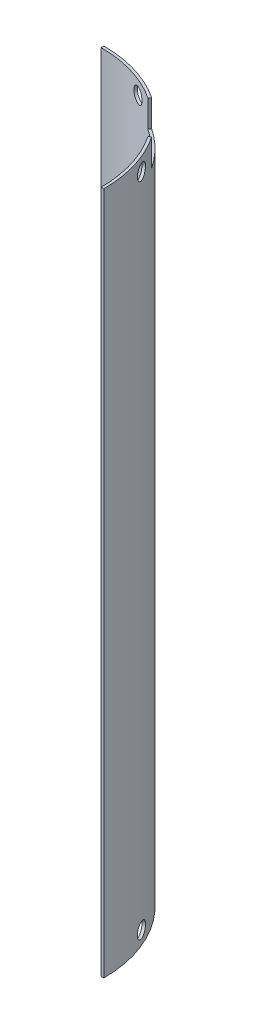
SolidWorks part; units mm, degrees
material "1060 Alloy"
ref_plane "Front Plane" through (0, 0, 0) normal (0, 0, 1) x (1, 0, 0)
ref_plane "Top Plane" through (0, 0, 0) normal (0, 1, 0) x (1, 0, 0)
ref_plane "Right Plane" through (0, 0, 0) normal (1, 0, 0) x (0, 0, -1)
sketch "Sketch1" plane through (0, 0, 0) normal (0, 1, 0) x (1, 0, 0)
  line L0 (0, 0) -> (0, 92)
  line L1 (0, 0) -> (92, 0)
  circle A0 centre (0, 0) radius 90
  circle A1 centre (0, 0) radius 92
  dimension "Internal Diameter" = 180
  dimension "External Diameter" = 184
extrude "Boss-Extrude1" add sketch "Sketch1" along normal blind 508.5 contours L1 A1 L0 A0
ref_plane "Plane1" through (0, 10, 0) normal (0, -1, 0) x (-1, 0, 0)
sketch "Sketch2" plane through (0, 10, 0) normal (0, -1, 0) x (-1, 0, 0)
  line L0 (0, 0) -> (-84.9969, 35.2069)
  line L1 (0, 0) -> (-65.0538, 65.0538)
  line L2 (0, 0) -> (-92, 0) construction
  line L3 (0, 0) -> (-35.2069, 84.9969)
  arc A0 (0, 92) -> (-92, 0) centre (0, 0) ccw construction
  dimension "D1" = 135
  dimension "D2" = 22.5
ref_plane "Plane2" through (84.9969, 0, -35.2069) normal (0.9239, 0, -0.3827) x (-0.3827, 0, -0.9239)
ref_plane "Plane3" through (35.2069, 0, -84.9969) normal (0.3827, 0, -0.9239) x (-0.9239, 0, -0.3827)
sketch "Sketch3" plane through (84.9969, 0, -35.2069) normal (0.9239, 0, -0.3827) x (-0.3827, 0, -0.9239)
  circle A0 centre (0, 10) radius 5.565
  point P0 (0, 10)
  dimension "Right Hole Diameter" = 11.13
sketch "Sketch5" plane through (35.2069, 0, -84.9969) normal (0.3827, 0, -0.9239) x (-0.9239, 0, -0.3827)
  line L0 (0, 10) -> (-84.9969, 10) construction
  circle A0 centre (0, 10) radius 5.565
  dimension "Left Hole Diameter" = 11.13
ref_plane "Plane4" through (65.0538, 0, -65.0538) normal (0.7071, 0, -0.7071) x (-0.7071, 0, -0.7071)
sketch "Sketch6" plane through (65.0538, 0, -65.0538) normal (0.7071, 0, -0.7071) x (-0.7071, 0, -0.7071)
  line L0 (0, 10) -> (-65.0538, 10) construction
  line L1 (0, 10) -> (35.2069, 10) construction
  circle A0 centre (0, 10) radius 5.565
  dimension "Middle Hole Diameter" = 11.13
extrude "Cut-Extrude4" cut sketch "Sketch6" against normal up to surface (2.1722 mm away)
extrude "Cut-Extrude2" cut sketch "Sketch3" against normal up to surface (2.1722 mm away) contours A0
extrude "Cut-Extrude3" cut sketch "Sketch5" against normal up to surface (2.1722 mm away) contours A0
pattern_linear "LPattern2" count 2 spacing 488.5 along (0, 1, 0) of "Cut-Extrude2", "Cut-Extrude3"
sketch "Sketch7" plane through (0, 0, 0) normal (0, -1, 0) x (1, 0, 0)
  line L0 (0, 0) -> (65.0538, -65.0538) construction
  line L1 (0.3118, -0.3118) -> (57.9282, -0.3118) construction
  line L2 (0.3118, -0.3118) -> (76.4474, -51.184)
  line L3 (0.3118, -0.3118) -> (51.184, -76.4474)
  line L6 (92, 0) -> (90, 0)
  line L7 (0, -90) -> (0, -92)
  line L8 (92, 0) -> (90, 0)
  line L9 (0, -90) -> (0, -92)
  arc A0 (0, -92) -> (92, 0) centre (0, 0) ccw construction
  arc A2 (0, -90) -> (90, 0) centre (0, 0) ccw
  arc A3 (0, -92) -> (92, 0) centre (0, 0) ccw
  arc A4 (0, -90) -> (90, 0) centre (0, 0) ccw
  arc A5 (0, -92) -> (92, 0) centre (0, 0) ccw
  arc M5 (90, 0) -> (0, -90) centre (0, 0) cw
  arc M7 (0, -92) -> (92, 0) centre (0, 0) ccw
  dimension "D1" = 45
  dimension "D2" = 11.25
  dimension "D3" = 0
extrude "Cut-Extrude5" cut sketch "Sketch7" against normal blind 20 contours L3 L2 M5 M7
move or copy body "Body-Move/Copy1" bodies to move or copy 107 copy no rotation origin (0, 252, 0) rotation axis (0.7071, 0, -0.7071) rotation angle 180
equation "\"Total Panel Length\"= 508.5"
equation "\"Internal Panel Diameter\"= 180"
equation "\"External Panel Diameter\"= 184"
equation "\"L & R Mounting Hole Diameter\"= 11.13"
equation "\"M Mounting Hole DIameter\" = 11.13"
equation "\"Mounting Hole Dist. from Top\"= 10"
equation "\"Mounting Hole Dist. from Base\" = 10"
equation "\"External Diameter@Sketch1\"= \"External Panel Diameter\""
equation "\"Internal Diameter@Sketch1\"= \"Internal Panel Diameter\""
equation "\"Panel Length@Boss-Extrude1\"= \"Total Panel Length\""
equation "\"Right Hole Diameter@Sketch3\"= \"L & R Mounting Hole Diameter\""
equation "\"Left Hole Diameter@Sketch5\"= \"L & R Mounting Hole Diameter\""
equation "\"Middle Hole Diameter@Sketch6\" = \"M Mounting Hole DIameter\""
equation "\"Mounting from Top@Plane1\"= \"Mounting Hole Dist. from Top\""
equation "\"Mounting from Base@LPattern2\"= \"Total Panel Length\" - \"Mounting Hole Dist. from Base\" - \"Mounting Hole Dist. from Top\""
equation "\"Top Tab Length@Cut-Extrude5\" = \"Top Tab Length\""
equation "\"Top Tab Length\" = 20"
